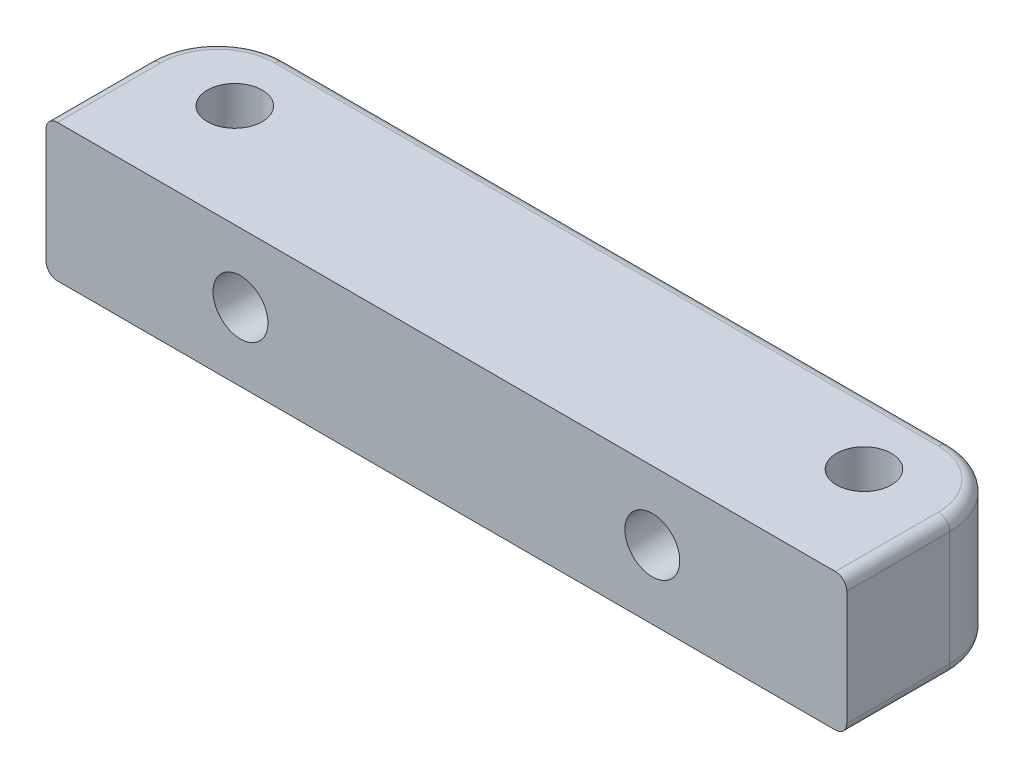
SolidWorks part; units mm, degrees
material "PET"
ref_plane "Front Plane" through (0, 0, 0) normal (0, 0, 1) x (1, 0, 0)
ref_plane "Top Plane" through (0, 0, 0) normal (0, 1, 0) x (1, 0, 0)
ref_plane "Right Plane" through (0, 0, 0) normal (1, 0, 0) x (0, 0, -1)
sketch "Sketch2" plane through (0, 0, 0) normal (0, 1, 0) x (1, 0, 0)
  line L1 (0, 113.4709) -> (0, 35.9943) construction
  line L2 (35, -7.5) -> (-35, -7.5)
  line L3 (35, -7.5) -> (35, 7.5)
  line L4 (35, 7.5) -> (-35, 7.5)
  line L5 (-35, -7.5) -> (-35, 7.5)
  line L6 (35, -7.5) -> (-35, 7.5) construction
  line L7 (35, 7.5) -> (-35, -7.5) construction
  circle A0 centre (-27.5, 1.5) radius 2.4
  circle A1 centre (27.5, 1.5) radius 2.4
  point P0 (0, 0)
  dimension "D3" = 4.8
  dimension "D1" = 70
  dimension "D2" = 15
  dimension "D4" = 6
extrude "Boss-Extrude1" add sketch "Sketch2" along normal mid plane 12
sketch "Sketch4" plane through (0, 0, 7.5) normal (0, 0, 1) x (1, 0, 0)
  line L0 (0, 0) -> (-18, 0) construction
  line L1 (0, 0) -> (0, -6) construction
  line L2 (-35, -6) -> (35, -6) construction
  circle A0 centre (-18, 0) radius 2.4
  circle A1 centre (18, 0) radius 2.4
  dimension "D1" = 18
  dimension "D2" = 4.8
extrude "Cut-Extrude1" cut sketch "Sketch4" against normal through all
fillet "Fillet1" radius 6 2 edges at (-35, 0, -7.5) (35, 0, -7.5)
fillet "Fillet2" radius 1 10 edges at (35, -6, 3) (33.2426, -6, -5.7426) (-35, -6, 3) (-33.2426, -6, -5.7426) (35, 6, 3) (33.2426, 6, -5.7426) (-35, 6, 3) (-33.2426, 6, -5.7426) (0, -6, -7.5) (0, 6, -7.5)
sketch "Sketch5" plane through (0, 0, -7.5) normal (0, 0, -1) x (-1, 0, 0)
  circle A0 centre (-18, 0) radius 4.5
  circle A1 centre (18, 0) radius 4.5
  point P5 (18, 0)
  dimension "D1" = 9
extrude "Cut-Extrude2" cut sketch "Sketch5" against normal blind 5
chamfer "Chamfer1" distance 0.4 angle 45 2 edges at (-22.5, 0, -7.5) (13.5, 0, -7.5)
equation "\"D3@Sketch2\"=4.8mm"
